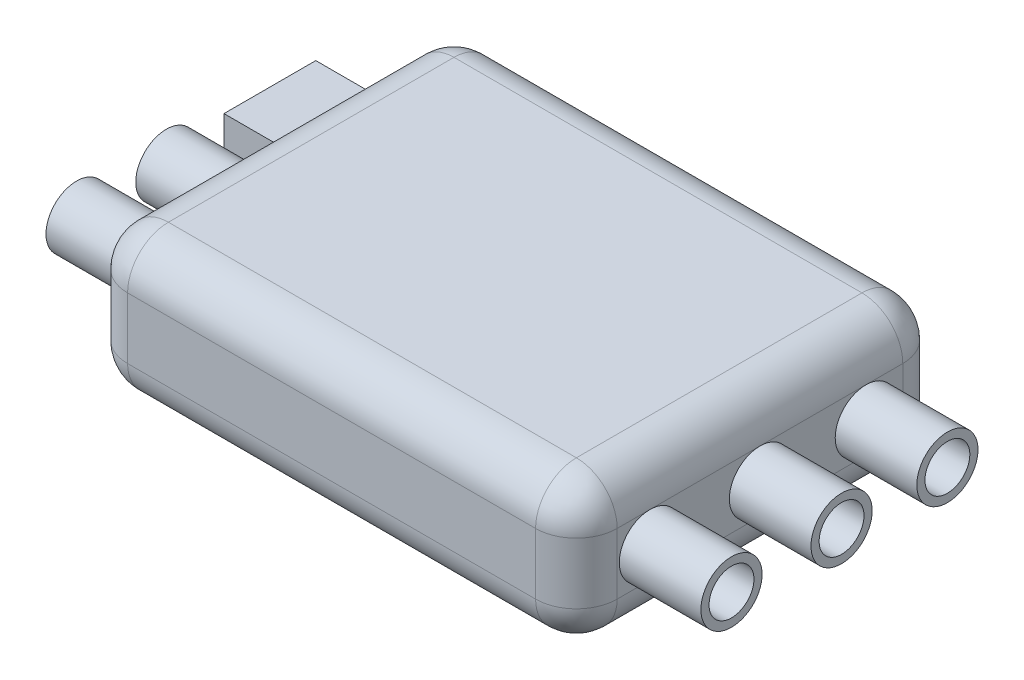
SolidWorks part; units mm, degrees
ref_plane "Front Plane" through (0, 0, 0) normal (0, 0, 1) x (1, 0, 0)
ref_plane "Top Plane" through (0, 0, 0) normal (0, 1, 0) x (1, 0, 0)
ref_plane "Right Plane" through (0, 0, 0) normal (1, 0, 0) x (0, 0, -1)
sketch "Sketch1" plane through (0, 0, 0) normal (0, 1, 0) x (1, 0, 0)
  line L1 (10, -9) -> (-10, -9)
  line L2 (12, -7) -> (12, 7)
  line L3 (10, 9) -> (-10, 9)
  line L4 (-12, -7) -> (-12, 7)
  line L5 (12, -9) -> (-12, 9) construction
  line L6 (12, 9) -> (-12, -9) construction
  arc A0 (-10, -9) -> (-12, -7) centre (-10, -7) cw
  arc A1 (12, 7) -> (10, 9) centre (10, 7) ccw
  arc A2 (10, -9) -> (12, -7) centre (10, -7) ccw
  arc A3 (-10, 9) -> (-12, 7) centre (-10, 7) ccw
  point P1 (0, 0)
  dimension "D3" = 2
  dimension "D1" = 24
  dimension "D2" = 18
extrude "Boss-Extrude1" add sketch "Sketch1" along normal blind 7
fillet "Fillet1" radius 2 8 edges at (-12, 7, 0) (-11.4142, 7, -8.4142) (0, 7, -9) (11.4142, 7, -8.4142) (12, 7, 0) (11.4142, 7, 8.4142) (0, 7, 9) (-11.4142, 7, 8.4142)
fillet "Fillet2" radius 2 8 edges at (0, 0, 9) (11.4142, 0, 8.4142) (12, 0, 0) (11.4142, 0, -8.4142) (0, 0, -9) (-11.4142, 0, -8.4142) (-12, 0, 0) (-11.4142, 0, 8.4142)
sketch "Sketch2" plane through (12, 0, 0) normal (1, 0, 0) x (0, 0, -1)
  line L0 (-7, 3.5) -> (7, 3.5) construction
  line L1 (-7, 5) -> (-7, 2) construction
  line L2 (7, 5) -> (7, 2) construction
  circle A0 centre (0, 3.5) radius 1.5
  circle A1 centre (0, 3.5) radius 1.1
  circle A2 centre (5.188, 3.5) radius 1.5
  circle A3 centre (5.188, 3.5) radius 1.1
  circle A4 centre (-5.3962, 3.5) radius 1.5
  circle A5 centre (-5.3962, 3.5) radius 1.1
  dimension "D1" = 3
  dimension "D2" = 0.4
extrude "Boss-Extrude2" add sketch "Sketch2" along normal blind 4
sketch "Sketch3" plane through (-12, 0, 0) normal (-1, 0, 0) x (0, 0, 1)
  line L0 (7, 3.5) -> (-7, 3.5) construction
  line L1 (7, 5) -> (7, 2) construction
  line L2 (-7, 5) -> (-7, 2) construction
  line L4 (-6.2245, 2.75) -> (-1.7245, 2.75)
  line L5 (-6.2245, 2.75) -> (-6.2245, 4.25)
  line L6 (-6.2245, 4.25) -> (-1.7245, 4.25)
  line L7 (-1.7245, 2.75) -> (-1.7245, 4.25)
  circle A0 centre (5.5, 3.5) radius 1.5
  circle A1 centre (5.5, 3.5) radius 1.1
  circle A2 centre (1.1, 3.5) radius 1.5
  circle A3 centre (1.1, 3.5) radius 1.1
  dimension "D3" = 3
  dimension "D4" = 0.4
  dimension "D1" = 4.5
  dimension "D2" = 1.5
  dimension "D5" = 4.4
extrude "Boss-Extrude3" add sketch "Sketch3" along normal blind 4
